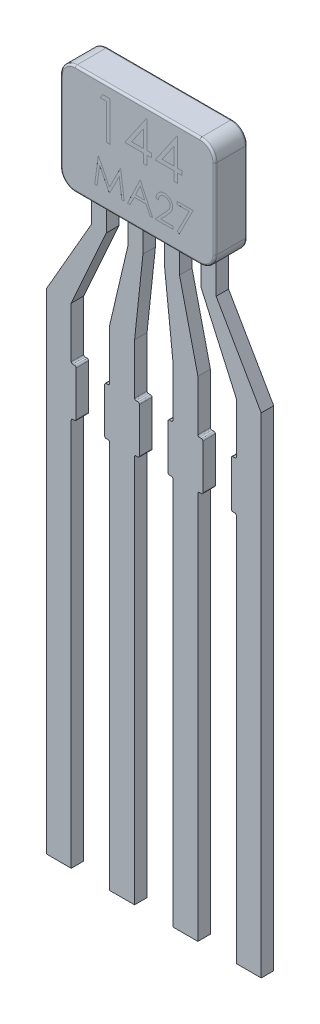
SolidWorks part; units mm, degrees
ref_plane "Front Plane" through (0, 0, 0) normal (0, 0, 1) x (1, 0, 0)
ref_plane "Top Plane" through (0, 0, 0) normal (0, 1, 0) x (1, 0, 0)
ref_plane "Right Plane" through (0, 0, 0) normal (1, 0, 0) x (0, 0, -1)
sketch "Sketch1" plane through (0, 0, 0) normal (0, 0, 1) x (1, 0, 0)
  line L1 (-1.25, 1.1) -> (1.25, 1.1)
  line L2 (-1.55, 0.8) -> (-1.55, -0.8)
  line L3 (-1.25, -1.1) -> (1.25, -1.1)
  line L4 (1.55, 0.8) -> (1.55, -0.8)
  line L5 (-1.55, 1.1) -> (1.55, -1.1) construction
  line L6 (-1.55, -1.1) -> (1.55, 1.1) construction
  arc A0 (-1.55, -0.8) -> (-1.25, -1.1) centre (-1.25, -0.8) ccw
  arc A1 (1.25, -1.1) -> (1.55, -0.8) centre (1.25, -0.8) ccw
  arc A2 (1.55, 0.8) -> (1.25, 1.1) centre (1.25, 0.8) ccw
  arc A3 (-1.25, 1.1) -> (-1.55, 0.8) centre (-1.25, 0.8) ccw
  point P0 (0, 0)
  dimension "D3" = 0.3
  dimension "D1" = 3.1
  dimension "D2" = 2.2
extrude "Boss-Extrude1" add sketch "Sketch1" along normal mid plane 0.65
fillet "Fillet1" radius 0.04 16 edges at (1.4621, -1.0121, -0.325) (0, -1.1, -0.325) (-1.4621, -1.0121, -0.325) (-1.55, 0, -0.325) (-1.4621, 1.0121, -0.325) (0, 1.1, -0.325) (1.4621, 1.0121, -0.325) (1.4621, 1.0121, 0.325) (1.55, 0, 0.325) (1.4621, -1.0121, 0.325) (0, -1.1, 0.325) (-1.4621, -1.0121, 0.325) (-1.55, 0, 0.325) (-1.4621, 1.0121, 0.325) (1.55, 0, -0.325) (0, 1.1, 0.325)
sketch "Sketch2" plane through (0, -1.1, 0) normal (0, -1, 0) x (1, 0, 0)
  line L0 (-1.25, 0.285) -> (-1.25, -0.285) construction
  line L1 (1.25, -0.2484) -> (-1.25, -0.2484)
  line L2 (1.25, -0.2484) -> (1.25, 0.2484)
  line L3 (1.25, 0.2484) -> (-1.25, 0.2484)
  line L4 (-1.25, -0.2484) -> (-1.25, 0.2484)
  line L5 (1.25, -0.2484) -> (-1.25, 0.2484) construction
  line L6 (1.25, 0.2484) -> (-1.25, -0.2484) construction
  point P0 (0, 0)
extrude "Cut-Extrude1" cut sketch "Sketch2" against normal blind 0.4
sketch "Sketch3" plane through (0, 0, -0.2484) normal (0, 0, 1) x (1, 0, 0)
  line L0 (-1.25, -0.7) -> (-1.25, -1.8136)
  line L1 (-1.25, -1.8136) -> (-2.155, -3.386)
  line L2 (-2.155, -3.386) -> (-2.155, -13.2)
  line L3 (1.25, 1.1) -> (-1.25, 1.1) construction
  line L4 (-2.155, -13.2) -> (-1.655, -13.2)
  line L5 (-1.655, -13.2) -> (-1.655, -5.4173)
  line L6 (-1.655, -3.386) -> (-0.95, -1.8136)
  line L7 (-0.95, -1.8136) -> (-0.95, -0.7)
  line L8 (-1.25, -0.7) -> (1.25, -0.7) construction
  line L9 (-0.95, -0.7) -> (-1.25, -0.7)
  line L10 (-0.5166, -0.7) -> (-0.5166, -1.8136)
  line L11 (-0.5166, -1.8136) -> (-0.885, -3.386)
  line L12 (-0.885, -3.386) -> (-0.885, -4.4006)
  line L13 (-0.885, -13.2) -> (-0.385, -13.2)
  line L14 (-0.385, -13.2) -> (-0.385, -5.4173)
  line L15 (-0.385, -3.386) -> (-0.2166, -1.8136)
  line L16 (-0.2166, -1.8136) -> (-0.2166, -0.7)
  line L17 (-0.2166, -0.7) -> (-0.5166, -0.7)
  line L18 (0, -0.3575) -> (0, 0.3575) construction
  line L20 (-1.625, -4.4306) -> (-1.585, -4.4306)
  line L21 (-1.555, -4.4606) -> (-1.555, -5.3573)
  line L22 (-1.585, -5.3873) -> (-1.625, -5.3873)
  line L23 (-0.915, -4.4306) -> (-0.955, -4.4306)
  line L24 (-0.985, -4.4606) -> (-0.985, -5.3573)
  line L25 (-0.955, -5.3873) -> (-0.915, -5.3873)
  line L26 (-0.355, -4.4306) -> (-0.315, -4.4306)
  line L27 (-0.285, -4.4606) -> (-0.285, -5.3573)
  line L28 (-0.315, -5.3873) -> (-0.355, -5.3873)
  line L29 (-1.655, -4.4006) -> (-1.655, -3.386)
  line L30 (-0.885, -5.4173) -> (-0.885, -13.2)
  line L31 (-0.385, -4.4006) -> (-0.385, -3.386)
  line L32 (-0.635, -13.2) -> (-0.635, -7.1461) construction
  line L33 (-1.905, -13.2) -> (-1.905, -6.8091) construction
  arc A0 (-0.385, -4.4006) -> (-0.355, -4.4306) centre (-0.355, -4.4006) ccw
  arc A1 (-0.315, -4.4306) -> (-0.285, -4.4606) centre (-0.315, -4.4606) cw
  arc A2 (-0.285, -5.3573) -> (-0.315, -5.3873) centre (-0.315, -5.3573) cw
  arc A3 (-0.355, -5.3873) -> (-0.385, -5.4173) centre (-0.355, -5.4173) ccw
  arc A4 (-0.915, -5.3873) -> (-0.885, -5.4173) centre (-0.915, -5.4173) cw
  arc A5 (-0.955, -5.3873) -> (-0.985, -5.3573) centre (-0.955, -5.3573) cw
  arc A6 (-0.885, -4.4006) -> (-0.915, -4.4306) centre (-0.915, -4.4006) cw
  arc A7 (-0.955, -4.4306) -> (-0.985, -4.4606) centre (-0.955, -4.4606) ccw
  arc A8 (-1.625, -5.3873) -> (-1.655, -5.4173) centre (-1.625, -5.4173) ccw
  arc A9 (-1.585, -5.3873) -> (-1.555, -5.3573) centre (-1.585, -5.3573) ccw
  arc A10 (-1.555, -4.4606) -> (-1.585, -4.4306) centre (-1.585, -4.4606) ccw
  arc A11 (-1.625, -4.4306) -> (-1.655, -4.4006) centre (-1.625, -4.4006) cw
  point P39 (-0.385, -4.4306)
  point P48 (-0.885, -5.3873)
  point P61 (-1.555, -4.4306)
  point P64 (-1.655, -4.4306)
  dimension "D8" = 0.03
  dimension "D1" = 14.3
  dimension "D2" = 0.5
  dimension "D3" = 0.3
  dimension "D4" = 0.2166
  dimension "D5" = 0.635
  dimension "D6" = 1.27
  dimension "D7" = 0.1
extrude "Boss-Extrude2" add sketch "Sketch3" along normal blind 0.25
mirror "Mirror1" about plane through (0, 0, 0) normal (1, 0, 0) of "Boss-Extrude2"
sketch "Sketch4" plane through (0, 0, 0.325) normal (0, 0, 1) x (1, 0, 0)
  text T0 "144\r\n" font "Century Gothic" height in points 3
  text T1 "MA27" font "Century Gothic" height in points 2
extrude "Cut-Extrude2" cut sketch "Sketch4" against normal blind 0.0001
